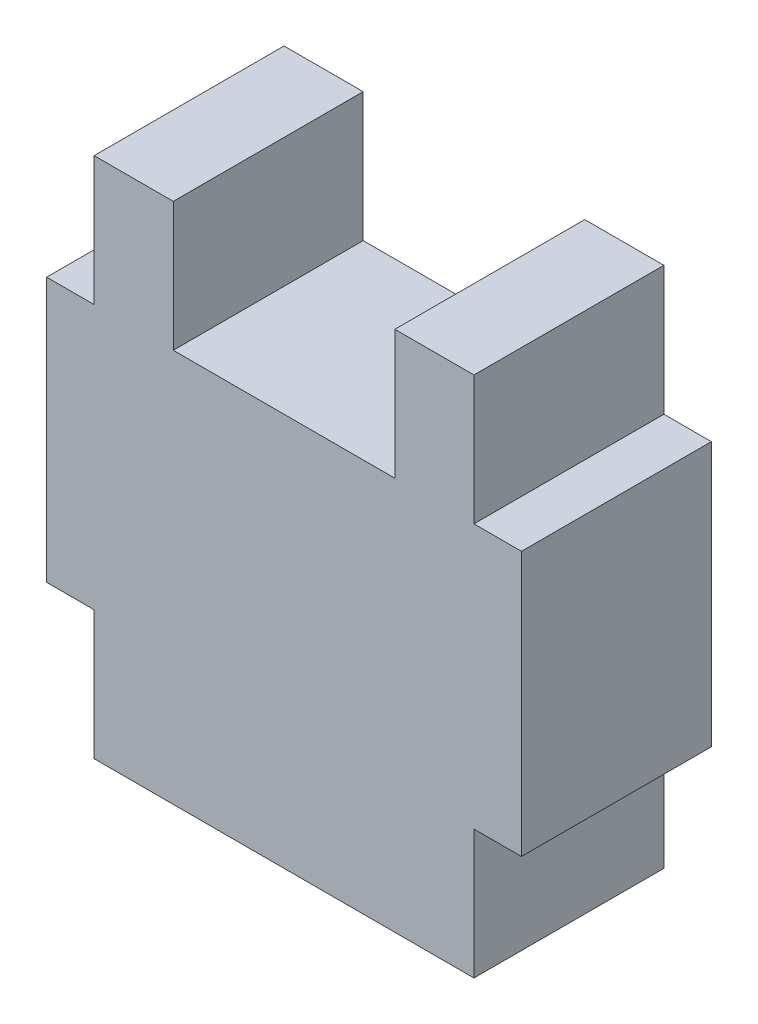
SolidWorks part; units mm, degrees
ref_plane "前视基准面" through (0, 0, 0) normal (0, 0, 1) x (1, 0, 0)
ref_plane "上视基准面" through (0, 0, 0) normal (0, 1, 0) x (1, 0, 0)
ref_plane "右视基准面" through (0, 0, 0) normal (1, 0, 0) x (0, 0, -1)
sketch "草图1" plane through (0, 0, 0) normal (0, 0, 1) x (1, 0, 0)
  line L0 (-1.5, -0.835) -> (-1.2, -0.835)
  line L1 (-1.2, -0.835) -> (-1.2, -1.65)
  line L2 (-1.2, -1.65) -> (1.2, -1.65)
  line L3 (1.2, -1.65) -> (1.2, -0.835)
  line L4 (1.2, -0.835) -> (1.5, -0.835)
  line L5 (1.5, -0.835) -> (1.5, 0.835)
  line L6 (1.5, 0.835) -> (1.2, 0.835)
  line L7 (1.2, 0.835) -> (1.2, 1.65)
  line L8 (1.2, 1.65) -> (0.7, 1.65)
  line L9 (0.7, 1.65) -> (0.7, 0.835)
  line L10 (0.7, 0.835) -> (-0.7, 0.835)
  line L11 (-0.7, 0.835) -> (-0.7, 1.65)
  line L12 (-0.7, 1.65) -> (-1.2, 1.65)
  line L13 (-1.2, 1.65) -> (-1.2, 0.835)
  line L14 (-1.2, 0.835) -> (-1.5, 0.835)
  line L15 (-1.5, 0.835) -> (-1.5, -0.835)
extrude "Component_Outline" add sketch "草图1" along normal blind 1.2 separate body
sketch3d "3D草图1"
  line L0 (0, 0, 0) -> (1, 0, 0)
  line L1 (0, 0, 0) -> (0, 1, 0)
  line L2 (0, 0, 0) -> (0, 0, 1)
  point P0 (0, 0, 0)
